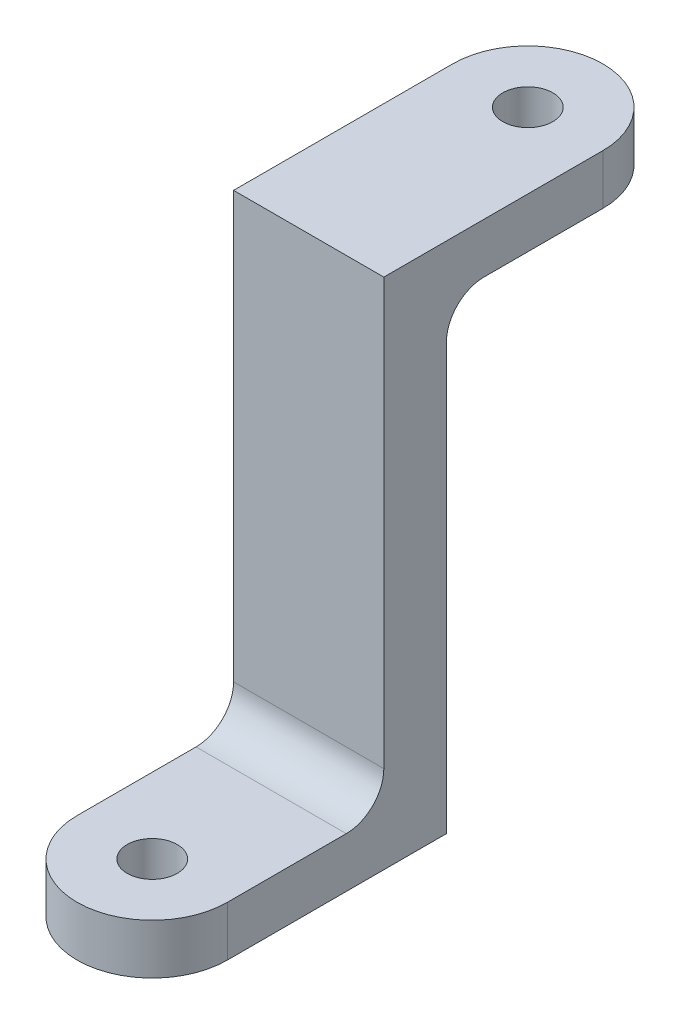
SolidWorks part; units mm, degrees
ref_plane "Front Plane" through (0, 0, 0) normal (0, 0, 1) x (1, 0, 0)
ref_plane "Top Plane" through (0, 0, 0) normal (0, 1, 0) x (1, 0, 0)
ref_plane "Right Plane" through (0, 0, 0) normal (1, 0, 0) x (0, 0, -1)
sketch "Sketch1" plane through (0, 0, 0) normal (0, 1, 0) x (1, 0, 0)
  line L0 (0, 30) -> (0, 0) construction
  line L1 (-6, 30) -> (-6, 0)
  line L2 (6, 30) -> (6, 0)
  circle A0 centre (0, 0) radius 2
  circle A1 centre (0, 30) radius 2
  circle A2 centre (0, 30) radius 6
  circle A3 centre (0, 0) radius 6
  dimension "D1" = 4
  dimension "D2" = 4
  dimension "D3" = 4
  dimension "D4" = 4
  dimension "D5" = 30
extrude "Boss-Extrude1" add sketch "Sketch1" along normal blind 4
sketch "Sketch2" plane through (0, 4, 0) normal (0, 1, 0) x (1, 0, 0)
  line L0 (-6, 30) -> (6, 0) construction
  line L1 (-6, 30) -> (-6, 0) construction
  line L2 (6, 17.5) -> (-6, 17.5)
  line L3 (6, 17.5) -> (6, 12.5)
  line L4 (6, 12.5) -> (-6, 12.5)
  line L5 (-6, 17.5) -> (-6, 12.5)
  line L6 (6, 17.5) -> (-6, 12.5) construction
  line L7 (6, 12.5) -> (-6, 17.5) construction
  point P4 (0, 15)
  dimension "D1" = 5
extrude "Boss-Extrude2" add sketch "Sketch2" along normal blind 33 contours L3 L2 L5 L4
sketch "Sketch3" plane through (0, 37, 0) normal (0, 1, 0) x (1, 0, 0)
  line L3 (-6, 17.5) -> (6, 17.5)
  line L4 (-6, 12.5) -> (6, 12.5)
  line L5 (6, 12.5) -> (6, 17.5)
  line L6 (6, 17.5) -> (-6, 17.5)
  line L7 (-6, 17.5) -> (-6, 12.5)
  line L8 (-6, 12.5) -> (6, 12.5)
  line L9 (6, 12.5) -> (6, 17.5)
  line L10 (6, 17.5) -> (-6, 17.5)
  line L11 (-6, 17.5) -> (-6, 12.5)
  line L12 (6, 17.5) -> (6, 30)
  line L13 (-6, 30) -> (-6, 17.5)
  line L14 (-6, 17.5) -> (6, 17.5)
  line L15 (6, 17.5) -> (6, 30)
  line L16 (-6, 30) -> (-6, 17.5)
  circle A0 centre (0, 30) radius 2
  arc A1 (6, 30) -> (-6, 30) centre (0, 30) ccw
  arc A2 (6, 30) -> (-6, 30) centre (0, 30) ccw
  line M9 (-6, 12.5) -> (6, 12.5)
  line M10 (6, 12.5) -> (6, 17.5)
  line M11 (6, 17.5) -> (-6, 17.5)
  line M12 (-6, 17.5) -> (-6, 12.5)
  dimension "D3" = 4
  dimension "D1" = 0
  dimension "D2" = 0
extrude "Boss-Extrude3" add sketch "Sketch3" along normal blind 4 contours L15 A2 L16 A0 M11 | M12 M9 M10 M11
fillet "Fillet1" radius 3 3 edges at (0, 4, -17.5) (0, 37, -17.5) (0, 4, -12.5)
sketch "Sketch4" plane through (0, 4, 0) normal (0, 1, 0) x (1, 0, 0)
  line L1 (-6, 36.9207) -> (6, 36.9207)
  line L2 (-6, 36.9207) -> (-6, 17.5)
  line L3 (-6, 17.5) -> (6, 17.5)
  line L4 (6, 36.9207) -> (6, 17.5)
extrude "Cut-Extrude1" cut sketch "Sketch4" against normal up to next and the other way blind 10
